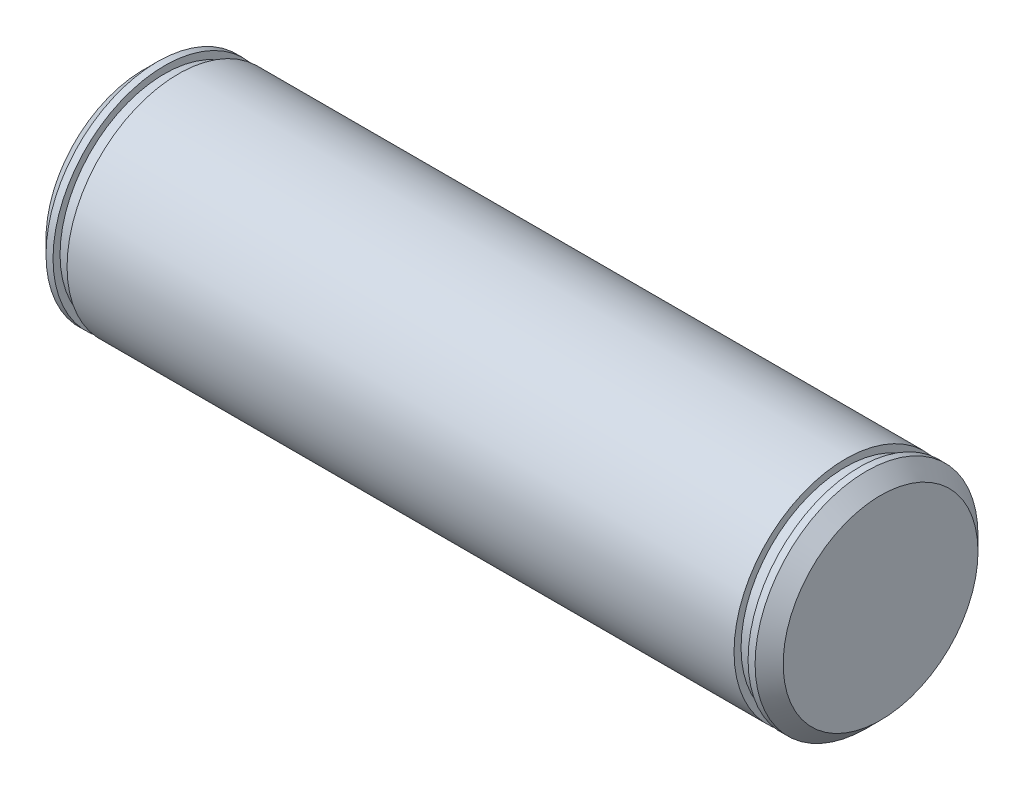
SolidWorks part; units mm, degrees
ref_plane "Front Plane" through (0, 0, 0) normal (0, 0, 1) x (1, 0, 0)
ref_plane "Top Plane" through (0, 0, 0) normal (0, 1, 0) x (1, 0, 0)
ref_plane "Right Plane" through (0, 0, 0) normal (1, 0, 0) x (0, 0, -1)
sketch "Sketch1" plane through (0, 0, 0) normal (1, 0, 0) x (0, 0, -1)
  circle A0 centre (0, 0) radius 15.875
  dimension "D1" = 31.75
extrude "Boss-Extrude1" add sketch "Sketch1" along normal mid plane 105
chamfer "Chamfer1" distance 2 angle 45 2 edges at (-52.5, 0, -15.875) (52.5, 0, -15.875)
ref_plane "Plane1" through (-47.5, 0, 0) normal (-1, 0, 0) x (0, 0, 1)
sketch "Sketch2" plane through (-47.5, 0, 0) normal (-1, 0, 0) x (0, 0, 1)
  circle A0 centre (0, 0) radius 15.875
  circle A1 centre (0, 0) radius 14.875
  dimension "D1" = 29.75
  dimension "D2" = 31.75
extrude "Cut-Extrude1" cut sketch "Sketch2" along normal blind 2
mirror "Mirror1" about plane through (0, 0, 0) normal (1, 0, 0) of "Cut-Extrude1"
